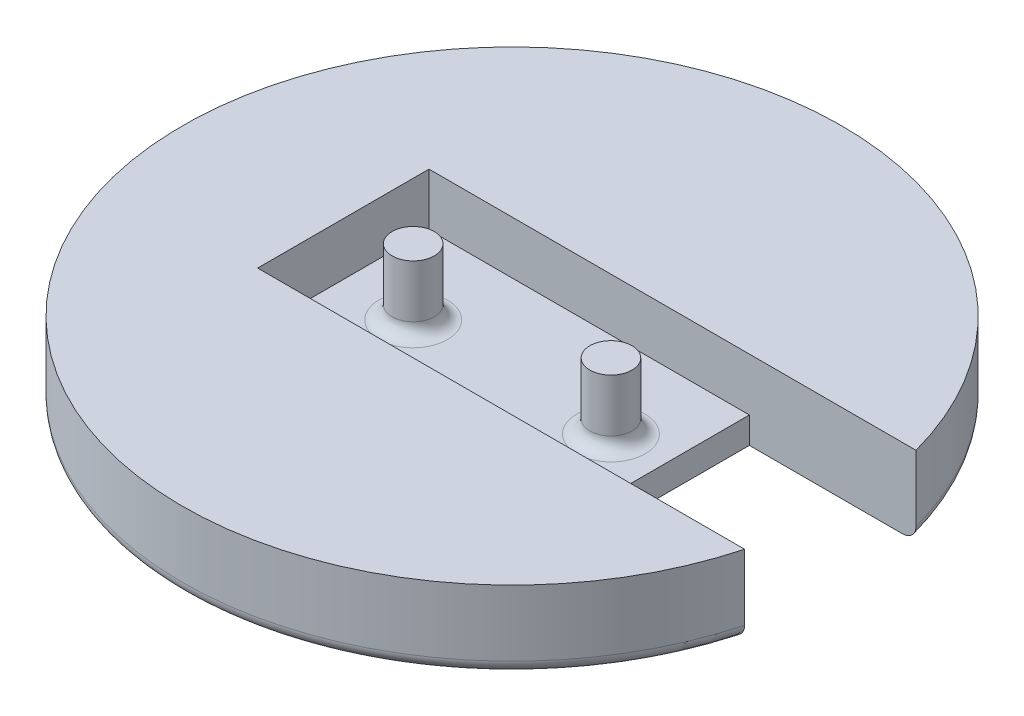
SolidWorks part; units mm, degrees
ref_plane "Front Plane" through (0, 0, 0) normal (0, 0, 1) x (1, 0, 0)
ref_plane "Top Plane" through (0, 0, 0) normal (0, 1, 0) x (1, 0, 0)
ref_plane "Right Plane" through (0, 0, 0) normal (1, 0, 0) x (0, 0, -1)
sketch "Sketch1" plane through (0, 0, 0) normal (0, 1, 0) x (1, 0, 0)
  line L0 (-25, 0) -> (25, 0) construction
  line L1 (0, 25) -> (0, -25) construction
  line L3 (-12.8, 6.5) -> (25, 6.5)
  line L4 (-12.8, 6.5) -> (-12.8, -6.5)
  line L5 (-12.8, -6.5) -> (25, -6.5)
  line L6 (25, 6.5) -> (25, -6.5)
  line L7 (6.1, -6.5) -> (6.1, 6.5) construction
  line L8 (-12.8, 0) -> (25, 0) construction
  circle A0 centre (0, 0) radius 25
  circle A1 centre (-7.5, 0) radius 1.6
  circle A2 centre (7.5, 0) radius 1.6
  point P11 (6.1, 0)
  dimension "D1" = 50
  dimension "D3" = 3.2
  dimension "D2" = 7.5
  dimension "D4" = 13
  dimension "D5" = 5.3
extrude "Boss-Extrude1" add sketch "Sketch1" along normal blind 2 contours L3 A0 L5 L4 | L5 A0 L3 L4 A1 A2 | A1 | A2
sketch "Sketch2" plane through (0, 2, 0) normal (0, 1, 0) x (1, 0, 0)
  line L0 (-12.8, -6.5) -> (25, -6.5) construction
  line L1 (-12.8, 6.5) -> (-12.8, -6.5) construction
  line L2 (-12.8, 6.5) -> (25, 6.5) construction
  line L3 (-12.8, -6.5) -> (25, -6.5)
  line L4 (-12.8, 6.5) -> (-12.8, -6.5)
  line L5 (-12.8, 6.5) -> (25, 6.5)
  circle A1 centre (0, 0) radius 25
  circle A2 centre (0, 0) radius 25
  circle M2 centre (0, 0) radius 25
  dimension "D1" = 0
extrude "Boss-Extrude2" add sketch "Sketch2" along normal blind 4 contours L4 L5 L3 M2
sketch "Sketch3" plane through (0, 2, 0) normal (0, 1, 0) x (1, 0, 0)
  line L0 (-12.8, 6.5) -> (25, 6.5) construction
  line L1 (11.5, 6.5) -> (25, 6.5)
  line L2 (11.5, 6.5) -> (11.5, -6.5)
  line L3 (11.5, -6.5) -> (25, -6.5)
  line L4 (25, 6.5) -> (25, -6.5)
  dimension "D1" = 4
extrude "Cut-Extrude1" cut sketch "Sketch3" against normal up to next
sketch "Sketch4" plane through (0, 2, 0) normal (0, 1, 0) x (1, 0, 0)
  circle A0 centre (7.5, 0) radius 1.6 construction
  circle A1 centre (-7.5, 0) radius 1.6 construction
  circle A2 centre (7.5, 0) radius 1.6
  circle A3 centre (-7.5, 0) radius 1.6
extrude "Boss-Extrude3" add sketch "Sketch4" along normal blind 5
fillet "Fillet1" radius 1 2 edges at (7.5, 2, 1.6) (-7.5, 2, 1.6)
fillet "Fillet2" radius 1 1 edges at (-25, 0, 0)
